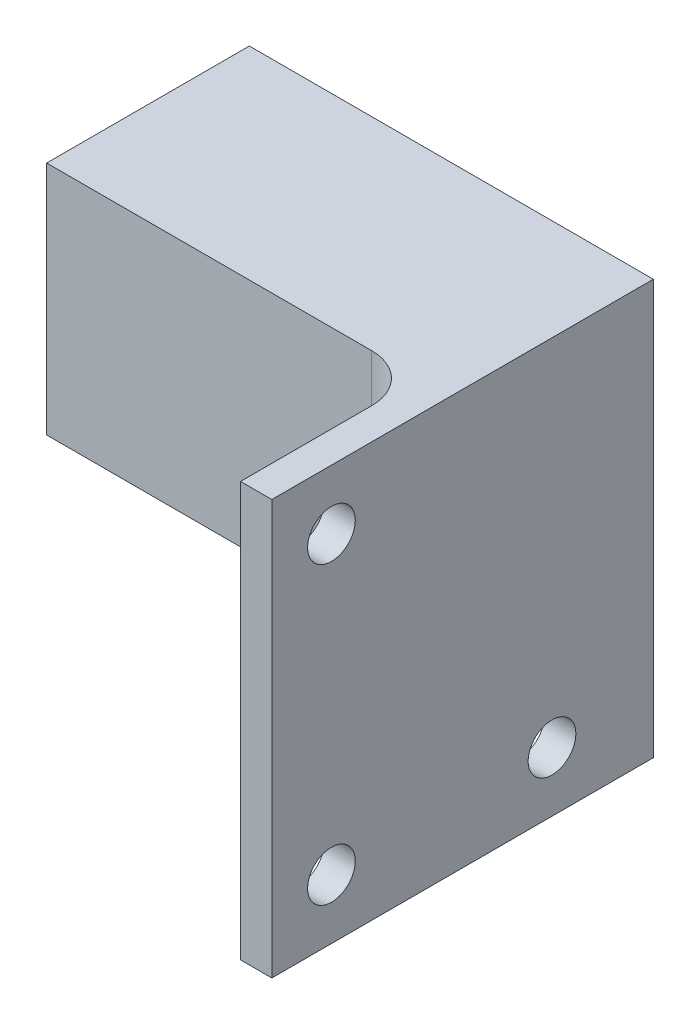
SolidWorks part; units mm, degrees
ref_plane "Front Plane" through (0, 0, 0) normal (0, 0, 1) x (1, 0, 0)
ref_plane "Top Plane" through (0, 0, 0) normal (0, 1, 0) x (1, 0, 0)
ref_plane "Right Plane" through (0, 0, 0) normal (1, 0, 0) x (0, 0, -1)
sketch "Sketch2" plane through (0, 0, 0) normal (0, 0, 1) x (1, 0, 0)
  line L0 (0, 0) -> (14.3189, -14.3189)
  line L1 (14.3189, -14.3189) -> (12.834, -15.8038)
  line L2 (12.834, -15.8038) -> (1.0607, -4.0305)
  line L3 (-1.0607, -4.0305) -> (-12.834, -15.8038)
  line L4 (-12.834, -15.8038) -> (-14.3189, -14.3189)
  line L5 (-14.3189, -14.3189) -> (0, 0)
  line L6 (-13.5765, -15.0614) -> (0, -1.4849) construction
  line L7 (0, -1.4849) -> (13.5765, -15.0614) construction
  line L8 (0, -2.9698) -> (0, -7.5866) construction
  line L10 (-16.9437, 2.2934) -> (16.9437, 2.2934)
  line L11 (-16.9437, 2.2934) -> (-16.9437, -17.4667)
  line L12 (-16.9437, -17.4667) -> (16.9437, -17.4667)
  line L13 (16.9437, 2.2934) -> (16.9437, -17.4667)
  line L14 (-16.9437, 2.2934) -> (16.9437, -17.4667) construction
  line L15 (-16.9437, -17.4667) -> (16.9437, 2.2934) construction
  arc A0 (1.0607, -4.0305) -> (-1.0607, -4.0305) centre (0, -5.0912) ccw
  point P15 (0, 0)
  point P16 (0, 0)
  dimension "D4" = 1.5
  dimension "D1" = 19.2
  dimension "D2" = 2.1
  dimension "D3" = 45
extrude "Boss-Extrude1" add sketch "Sketch2" along normal blind 15
sketch "Sketch3" plane through (0, 0, 15) normal (0, 0, 1) x (1, 0, 0)
  line L4 (16.9437, -17.4667) -> (16.9437, 2.2934)
  line L5 (16.9437, 2.2934) -> (-16.9437, 2.2934)
  line L6 (-16.9437, 2.2934) -> (-16.9437, -17.4667)
  line L7 (-16.9437, -17.4667) -> (16.9437, -17.4667)
  line L8 (16.9437, -17.4667) -> (16.9437, 2.2934)
  line L9 (16.9437, 2.2934) -> (-16.9437, 2.2934)
  line L10 (-16.9437, 2.2934) -> (-16.9437, -17.4667)
  line L11 (-16.9437, -17.4667) -> (16.9437, -17.4667)
  dimension "D1" = 0
extrude "Boss-Extrude2" add sketch "Sketch3" along normal blind 2
sketch "Sketch6" plane through (16.9437, 0, 0) normal (1, 0, 0) x (0, 0, -1)
  line L0 (-17, -17.4667) -> (-17, 2.2934) construction
  line L1 (0, 2.2934) -> (-32, 2.2934)
  line L2 (0, 2.2934) -> (0, -32.4667)
  line L3 (0, -32.4667) -> (-32, -32.4667)
  line L4 (-32, 2.2934) -> (-32, -32.4667)
  line L5 (-17, -17.4667) -> (0, -17.4667) construction
  line L6 (-17, 2.2934) -> (-32, 2.2934) construction
  line L7 (0, -17.4667) -> (0, -32.4667) construction
  line L8 (-27, -2.7066) -> (-27, -27.4667) construction
  line L9 (-27, -27.4667) -> (-8.5, -27.4667) construction
  circle A0 centre (-8.5, -27.4667) radius 2
  circle A1 centre (-27, -27.4667) radius 2
  circle A2 centre (-27, -2.7066) radius 2
  dimension "D3" = 4
  dimension "D1" = 15
  dimension "D2" = 15
  dimension "D4" = 5
  dimension "D5" = 5
  dimension "D6" = 5
extrude "Boss-Extrude4" add sketch "Sketch6" against normal up to vertex (2.6248 mm away) up to point (14.3189, -14.3189, 0)
fillet "Fillet1" radius 4 2 edges at (14.3189, -7.5866, 17) (14.3189, -17.4667, 8.5)
